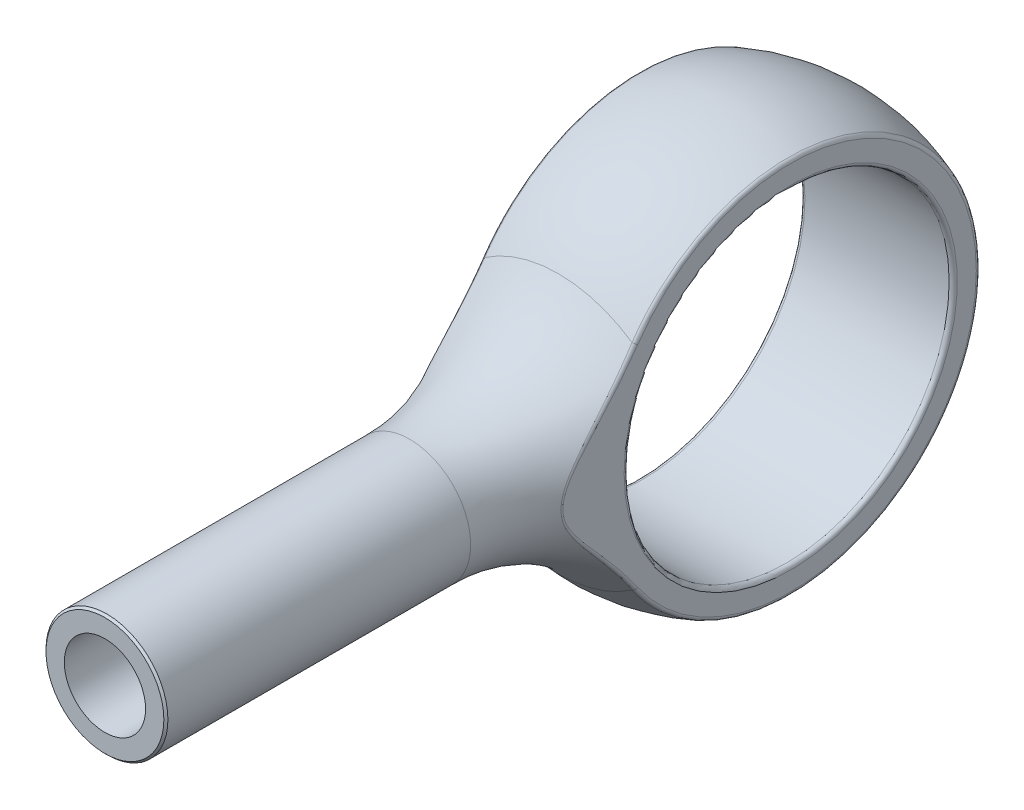
SolidWorks part; units mm, degrees
ref_plane "Front Plane" through (0, 0, 0) normal (0, 0, 1) x (1, 0, 0)
ref_plane "Top Plane" through (0, 0, 0) normal (0, 1, 0) x (1, 0, 0)
ref_plane "Right Plane" through (0, 0, 0) normal (1, 0, 0) x (0, 0, -1)
sketch "Sketch1" plane through (0, 0, 0) normal (0, 1, 0) x (1, 0, 0)
  line L0 (-1.5, -15) -> (1.5, -15)
  line L1 (-1.5, -15) -> (-1.5, -7.5)
  line L2 (1.5, -15) -> (1.5, -7.5)
  circle A0 centre (0, 0) radius 2
  circle A1 centre (0, 0) radius 4
  circle A2 centre (0, 0) radius 5
  arc A3 (-3.1997, -3.8421) -> (-1.5, -7.5) centre (-6.221, -7.4699) cw
  arc A4 (1.5, -7.5) -> (3.4033, -3.663) centre (6.4996, -7.5895) cw
  point P7 (0, -15)
  dimension "D1" = 4
  dimension "D2" = 8
  dimension "D3" = 10
  dimension "D4" = 3
  dimension "D5" = 15
  dimension "D6" = 7.5
sketch "Sketch2" plane through (0, 0, 0) normal (0, 1, 0) x (1, 0, 0)
  line L0 (-1.5, -15) -> (1.5, -15) construction
  line L1 (-1.5, -15) -> (-1.5, -7.5) construction
  line L2 (-1.5, -15) -> (0, -15)
  line L3 (-1.5, -15) -> (-1.5, -7.5)
  line L4 (0, 5) -> (0, -15)
  arc A0 (-1.5, -7.5) -> (-3.1997, -3.8421) centre (-6.221, -7.4699) ccw construction
  arc A1 (-1.5, -7.5) -> (-3.1997, -3.8421) centre (-6.221, -7.4699) ccw
  circle A2 centre (0, 0) radius 5 construction
  arc A3 (0, 5) -> (-3.1997, -3.8421) centre (0, 0) ccw
revolve "Revolve1" add sketch "Sketch2" angle 360 about L4
sketch "Sketch3" plane through (0, 0, 0) normal (0, 1, 0) x (1, 0, 0)
  line L0 (0, 0) -> (0, 7.943) construction
  line L1 (1.875, -5.8551) -> (1.875, 9.3727)
  line L2 (1.875, 9.3727) -> (7.4807, 9.3727)
  line L3 (7.4807, 9.3727) -> (7.4807, -15.4373)
  line L4 (7.4807, -15.4373) -> (2.7792, -8.723)
  line L5 (-1.875, 9.3727) -> (-7.4807, 9.3727)
  line L6 (-1.875, -5.8551) -> (-1.875, 9.3727)
  line L7 (-7.4807, -15.4373) -> (-2.7792, -8.723)
  line L8 (-7.4807, 9.3727) -> (-7.4807, -15.4373)
  arc A0 (-1.875, -5.8551) -> (-2.7792, -8.723) centre (-6.875, -5.8551) cw
  arc A1 (1.875, -5.8551) -> (2.7792, -8.723) centre (6.875, -5.8551) ccw
  point P13 (-1.875, -7.4316)
  point P16 (1.875, -7.4316)
  dimension "D2" = 5
  dimension "D1" = 3.75
  dimension "D3" = 145
extrude "Cut-Extrude2" cut sketch "Sketch3" against normal mid plane 20
sketch "Sketch5" plane through (0, 0, 0) normal (1, 0, 0) x (0, 0, -1)
  circle A0 centre (0, 0) radius 4
  dimension "D1" = 8
extrude "Cut-Extrude3" cut sketch "Sketch5" against normal mid plane 20
fillet "Fillet1" radius 0.1 6 edges at (1.875, 0.1977, 5.6014) (-1.875, -0.1977, 5.6014) (1.875, 0, 4) (1.875, 0, -4.6351) (-1.875, 0, -4.6351) (-1.875, 0, -4)
sketch "Sketch6" plane through (0, 0, 15) normal (0, 0, 1) x (1, 0, 0)
  line L0 (5, 0) -> (-5, 0) construction
  circle A0 centre (0, 0) radius 1
  dimension "D1" = 2
extrude "Cut-Extrude4" cut sketch "Sketch6" against normal blind 5
chamfer "Chamfer1" distance 0.05 angle 45 1 edges at (-1.5, 0, 15)
